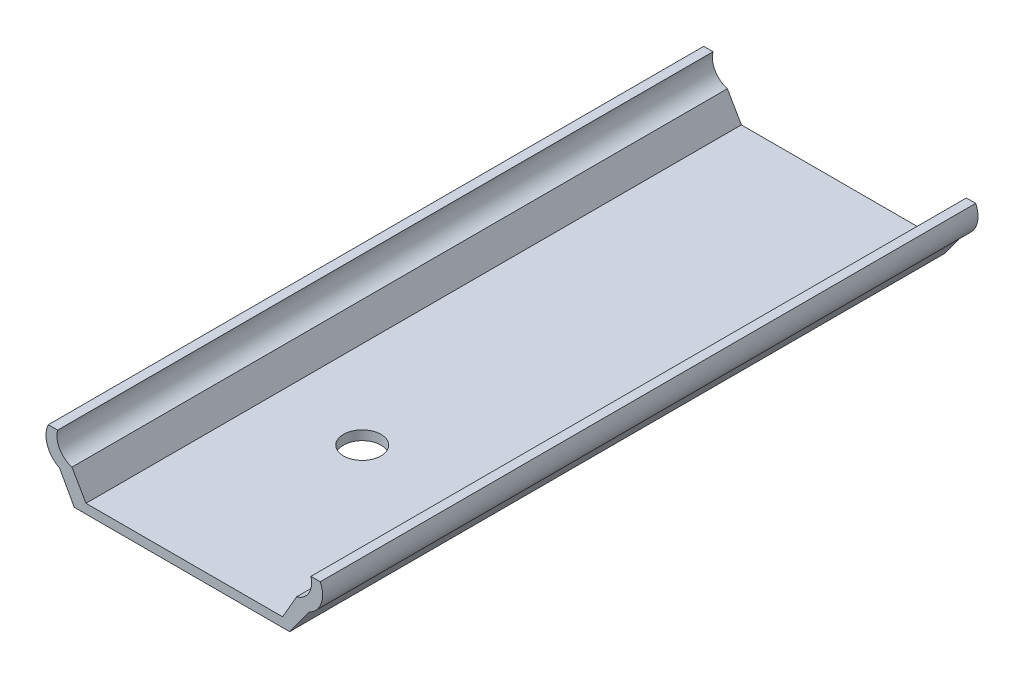
SolidWorks part; units mm, degrees
ref_plane "Plan de face" through (0, 0, 0) normal (0, 0, 1) x (1, 0, 0)
ref_plane "Plan de dessus" through (0, 0, 0) normal (0, 1, 0) x (1, 0, 0)
ref_plane "Plan de droite" through (0, 0, 0) normal (1, 0, 0) x (0, 0, -1)
sketch "Esquisse1" plane through (0, 0, 0) normal (0, 0, 1) x (1, 0, 0)
  line L0 (-10.5, 0) -> (10.5, 0)
  line L1 (-13.5246, 5.2568) -> (-14.5246, 5.2568)
  line L2 (-10.5, 0) -> (-11.9961, 2.6003)
  line L3 (-11.7501, -1) -> (11.2499, -1)
  line L4 (-13.3106, 1.844) -> (-11.7501, -1)
  line L5 (0, 0) -> (0, 11.4032) construction
  line L6 (11.2499, -1) -> (13.3106, 1.844)
  line L7 (13.5246, 5.2568) -> (14.5246, 5.2568)
  line L8 (10.5, 0) -> (11.9961, 2.6003)
  arc A0 (-11.9961, 2.6003) -> (-13.5246, 5.2568) centre (-11.4321, 4.6928) cw
  arc A1 (-14.5246, 5.2568) -> (-13.3106, 1.844) centre (-12.2112, 4.1574) ccw
  arc A2 (14.5246, 5.2568) -> (13.3106, 1.844) centre (12.2112, 4.1574) cw
  arc A3 (11.9961, 2.6003) -> (13.5246, 5.2568) centre (11.4321, 4.6928) ccw
  point P4 (0, 0)
  point P8 (-0.1533, -2.1493)
  point P13 (-0.2501, -1)
  dimension "D1" = 21
  dimension "D2" = 1
  dimension "D3" = 3
  dimension "D4" = 23
extrude "Boss.-Extru.1" add sketch "Esquisse1" along normal blind 70
sketch "Esquisse2" plane through (0, -1, 0) normal (0, -1, 0) x (1, 0, 0)
  line L0 (-0.2501, 70) -> (-0.2501, 13) construction
  line L1 (-11.7501, 70) -> (11.2499, 70) construction
  dimension "D1" = 57
extrude "Enlèv. mat.-Extru.1" [suppressed] cut sketch "Esquisse2" against normal blind 10
sketch "Esquisse3" plane through (0, -1, 0) normal (0, -1, 0) x (1, 0, 0)
  line L0 (-11.7501, 70) -> (11.2499, 70) construction
  line L1 (14.7725, 0) -> (14.7725, 70) construction
  circle A1 centre (-0.2501, 50) radius 2
  dimension "D2" = 4
  dimension "D3" = 15.0227
  dimension "D1" = 20
extrude "Enlèv. mat.-Extru.2" [suppressed] cut sketch "Esquisse3" against normal blind 10
sketch "Esquisse4" plane through (0, -1, 0) normal (0, -1, 0) x (1, 0, 0)
  line L0 (0, 0) -> (0, 16)
  dimension "D1" = 16
extrude "Enlèv. mat.-Extru.3" [suppressed] cut sketch "Esquisse4" against normal blind 10
sketch "Sketch1" plane through (0, -1, 0) normal (0, -1, 0) x (1, 0, 0)
  circle A0 centre (-1.1304, 49.8684) radius 2
  dimension "D1" = 4
extrude "Cut-Extrude1" cut sketch "Sketch1" against normal blind 10
